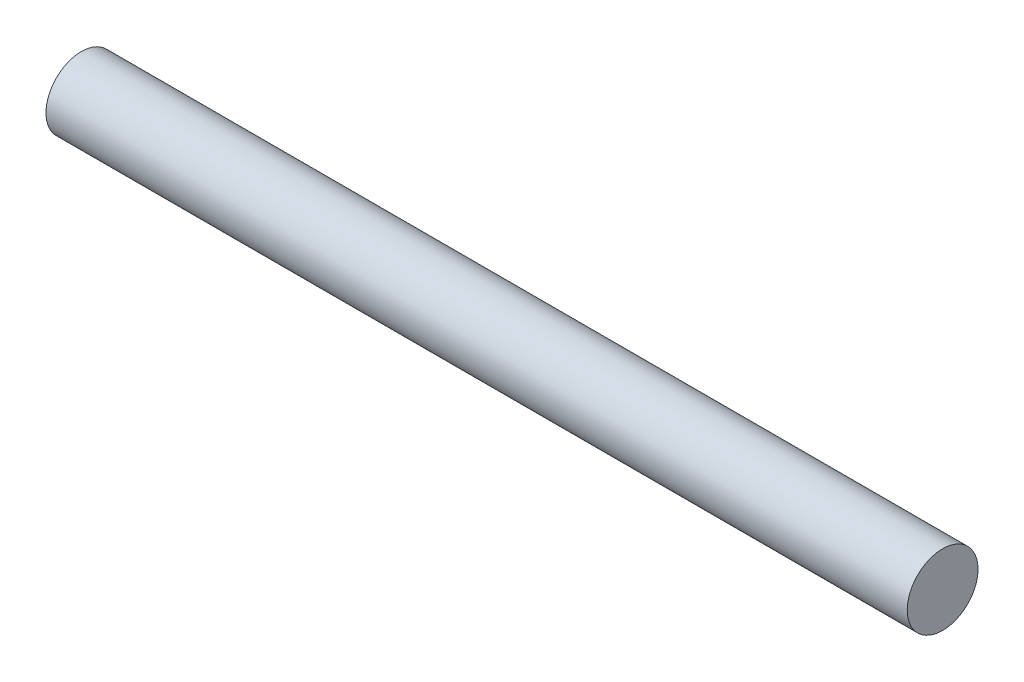
SolidWorks part; units mm, degrees
ref_plane "Front Plane" through (0, 0, 0) normal (0, 0, 1) x (1, 0, 0)
ref_plane "Top Plane" through (0, 0, 0) normal (0, 1, 0) x (1, 0, 0)
ref_plane "Right Plane" through (0, 0, 0) normal (1, 0, 0) x (0, 0, -1)
sketch "Sketch1" plane through (0, 0, 0) normal (1, 0, 0) x (0, 0, -1)
  circle A0 centre (0, 0) radius 3.57
  dimension "D1" = 7.14
extrude "Boss-Extrude1" add sketch "Sketch1" along normal up to surface (86.8566 mm away)
